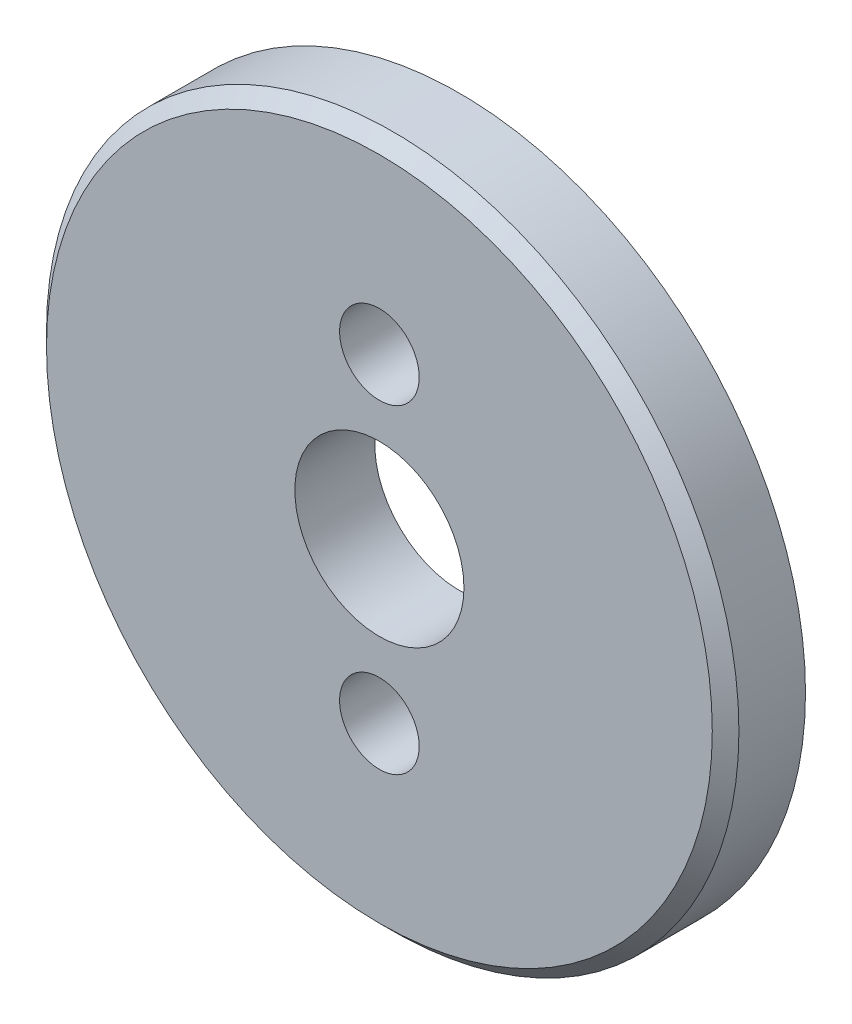
SolidWorks part; units mm, degrees
ref_plane "Спереди" through (0, 0, 0) normal (0, 0, 1) x (1, 0, 0)
ref_plane "Сверху" through (0, 0, 0) normal (0, 1, 0) x (1, 0, 0)
ref_plane "Справа" through (0, 0, 0) normal (1, 0, 0) x (0, 0, -1)
sketch "Эскиз1" plane through (0, 0, 0) normal (0, 0, 1) x (1, 0, 0)
  circle A0 centre (0, 0) radius 13
  circle A1 centre (0, 0) radius 3.175
  circle A2 centre (0, 6) radius 1.4944
  circle A3 centre (0, -6) radius 1.4944
  dimension "D1" = 6.35
  dimension "D2" = 26
  dimension "D3" = 6
extrude "Вытянуть1" add sketch "Эскиз1" along normal blind 3
chamfer "Фаска1" distance 0.5 angle 45 1 edges at (13, 0, 3)
